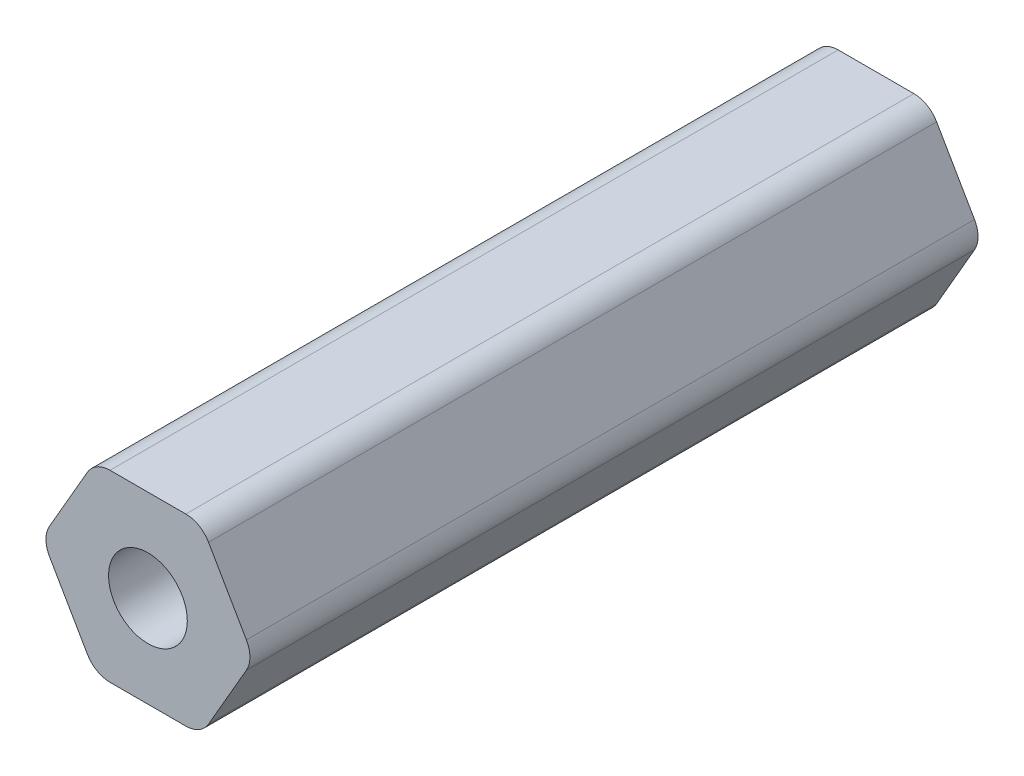
SolidWorks part; units mm, degrees
material "ABS"
ref_plane "Спереди" through (0, 0, 0) normal (0, 0, 1) x (1, 0, 0)
ref_plane "Сверху" through (0, 0, 0) normal (0, 1, 0) x (1, 0, 0)
ref_plane "Справа" through (0, 0, 0) normal (1, 0, 0) x (0, 0, -1)
sketch "Эскиз1" plane through (0, 0, 0) normal (0, 0, 1) x (1, 0, 0)
  line L1 (3.7528, 0.5) -> (2.3094, 3)
  line L2 (1.4434, 3.5) -> (-1.4434, 3.5)
  line L3 (-2.3094, 3) -> (-3.7528, 0.5)
  line L4 (-3.7528, -0.5) -> (-2.3094, -3)
  line L5 (-1.4434, -3.5) -> (1.4434, -3.5)
  line L6 (2.3094, -3) -> (3.7528, -0.5)
  circle A0 centre (0, 0) radius 3.5 construction
  circle A1 centre (0, 0) radius 1.5
  arc A2 (-3.7528, 0.5) -> (-3.7528, -0.5) centre (-2.8868, 0) ccw
  arc A3 (-2.3094, -3) -> (-1.4434, -3.5) centre (-1.4434, -2.5) ccw
  arc A4 (1.4434, -3.5) -> (2.3094, -3) centre (1.4434, -2.5) ccw
  arc A5 (3.7528, 0.5) -> (3.7528, -0.5) centre (2.8868, 0) cw
  arc A6 (2.3094, 3) -> (1.4434, 3.5) centre (1.4434, 2.5) ccw
  arc A7 (-1.4434, 3.5) -> (-2.3094, 3) centre (-1.4434, 2.5) ccw
  dimension "D1" = 3
  dimension "D3" = 1
  dimension "D2" = 7
extrude "Бобышка-Вытянуть1" add sketch "Эскиз1" along normal blind 27.75
